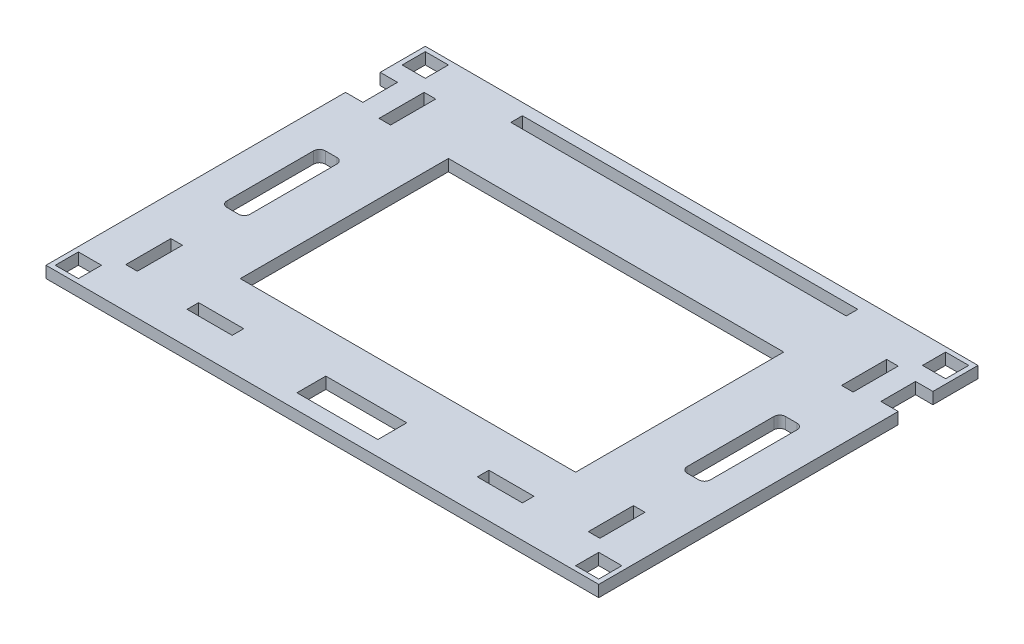
SolidWorks part; units mm, degrees
ref_plane "Front Plane" through (0, 0, 0) normal (0, 0, 1) x (1, 0, 0)
ref_plane "Top Plane" through (0, 0, 0) normal (0, 1, 0) x (1, 0, 0)
ref_plane "Right Plane" through (0, 0, 0) normal (1, 0, 0) x (0, 0, -1)
sketch "Sketch1" plane through (0, 0, 0) normal (0, 1, 0) x (1, 0, 0)
  line L1 (-239, 146.2945) -> (239, 146.2945)
  line L2 (-239, 146.2945) -> (-239, -181.7055)
  line L3 (-239, -181.7055) -> (239, -181.7055)
  line L4 (239, 146.2945) -> (239, -181.7055)
  dimension "D1" = 328
  dimension "D2" = 478
extrude "Boss-Extrude1" add sketch "Sketch1" along normal blind 10
sketch "Sketch2" plane through (0, 10, 0) normal (0, 1, 0) x (1, 0, 0)
  line L0 (239, 146.2945) -> (-239, 146.2945) construction
  line L1 (-235, 142.2945) -> (-215, 142.2945)
  line L2 (-235, 142.2945) -> (-235, 122.2945)
  line L3 (-235, 122.2945) -> (-215, 122.2945)
  line L4 (-215, 142.2945) -> (-215, 122.2945)
  line L5 (-239, 146.2945) -> (-239, -181.7055) construction
  line L6 (-235, -157.7055) -> (-215, -157.7055)
  line L7 (-235, -157.7055) -> (-235, -177.7055)
  line L8 (-235, -177.7055) -> (-215, -177.7055)
  line L9 (-215, -157.7055) -> (-215, -177.7055)
  line L10 (-239, -181.7055) -> (239, -181.7055) construction
  line L11 (215, 142.2945) -> (235, 142.2945)
  line L12 (215, 142.2945) -> (215, 122.2945)
  line L13 (215, 122.2945) -> (235, 122.2945)
  line L14 (235, 142.2945) -> (235, 122.2945)
  line L15 (215, -157.7055) -> (235, -157.7055)
  line L16 (215, -157.7055) -> (215, -177.7055)
  line L17 (215, -177.7055) -> (235, -177.7055)
  line L18 (235, -157.7055) -> (235, -177.7055)
  line L19 (239, -181.7055) -> (239, 146.2945) construction
  dimension "D1" = 20
  dimension "D2" = 20
  dimension "D3" = 4
  dimension "D4" = 4
  dimension "D5" = 4
  dimension "D6" = 4
  dimension "D7" = 20
  dimension "D8" = 20
  dimension "D9" = 20
  dimension "D10" = 4
  dimension "D11" = 4
  dimension "D12" = 20
  dimension "D13" = 4
  dimension "D14" = 4
  dimension "D15" = 20
  dimension "D16" = 20
extrude "Cut-Extrude1" cut sketch "Sketch2" against normal up to next
sketch "Sketch3" plane through (0, 10, 0) normal (0, 1, 0) x (1, 0, 0)
  line L0 (239, -17.7055) -> (-239, -17.7055) construction
  line L1 (239, -181.7055) -> (239, 146.2945) construction
  line L2 (-239, 146.2945) -> (-239, -181.7055) construction
  line L3 (0, 168.3588) -> (0, -221.3758) construction
  line L4 (239, 146.2945) -> (-239, 146.2945) construction
  line L5 (-145, 126.2945) -> (145, 126.2945)
  line L6 (-145, 126.2945) -> (-145, 136.2945)
  line L7 (-145, 136.2945) -> (145, 136.2945)
  line L8 (145, 136.2945) -> (145, 126.2945)
  line L9 (0, 126.2945) -> (-195, 126.2945) construction
  line L10 (-195, 111.2945) -> (-205, 111.2945)
  line L11 (-205, 111.2945) -> (-205, 72.2945)
  line L12 (-205, 72.2945) -> (-195, 72.2945)
  line L13 (-195, 72.2945) -> (-195, 111.2945)
  line L14 (-195, 126.2945) -> (-195, 119.0463) construction
  line L15 (195, 72.2945) -> (195, 111.2945)
  line L16 (205, 72.2945) -> (195, 72.2945)
  line L17 (205, 111.2945) -> (205, 72.2945)
  line L18 (195, 111.2945) -> (205, 111.2945)
  line L19 (195, -146.7055) -> (205, -146.7055)
  line L20 (205, -146.7055) -> (205, -107.7055)
  line L21 (205, -107.7055) -> (195, -107.7055)
  line L22 (195, -107.7055) -> (195, -146.7055)
  line L23 (-195, -107.7055) -> (-195, -146.7055)
  line L24 (-205, -107.7055) -> (-195, -107.7055)
  line L25 (-205, -146.7055) -> (-205, -107.7055)
  line L26 (-195, -146.7055) -> (-205, -146.7055)
  line L27 (-145, -143.7055) -> (-106, -143.7055)
  line L28 (-145, -143.7055) -> (-145, -153.7055)
  line L29 (-145, -153.7055) -> (-106, -153.7055)
  line L30 (145, -153.7055) -> (145, -143.7055)
  line L31 (-106, -143.7055) -> (-106, -153.7055)
  line L32 (106, -143.7055) -> (106, -153.7055)
  line L33 (106, -153.7055) -> (145, -153.7055)
  line L34 (106, -143.7055) -> (145, -143.7055)
  line L35 (35, -143.7055) -> (-35, -143.7055)
  line L36 (-35, -143.7055) -> (-35, -168.7055)
  line L37 (-35, -168.7055) -> (35, -168.7055)
  line L38 (35, -168.7055) -> (35, -143.7055)
  line L39 (209, 24.7945) -> (189, -60.2055) construction
  line L40 (-204, -60.2055) -> (-194, -60.2055)
  line L41 (-209, -55.2055) -> (-209, 19.7945)
  line L42 (-204, 24.7945) -> (-194, 24.7945)
  line L43 (-189, -55.2055) -> (-189, 19.7945)
  line L44 (-209, -60.2055) -> (-189, 24.7945) construction
  line L45 (-209, 24.7945) -> (-189, -60.2055) construction
  line L46 (209, -60.2055) -> (189, 24.7945) construction
  line L47 (189, -55.2055) -> (189, 19.7945)
  line L48 (204, 24.7945) -> (194, 24.7945)
  line L49 (209, -55.2055) -> (209, 19.7945)
  line L50 (204, -60.2055) -> (194, -60.2055)
  line L51 (145, 72.2945) -> (-145, 72.2945)
  line L52 (-145, 72.2945) -> (-145, -107.7055)
  line L53 (-145, -107.7055) -> (145, -107.7055)
  line L54 (145, -107.7055) -> (145, 72.2945)
  line L55 (-239, 107.2945) -> (-224, 107.2945)
  line L56 (-224, 107.2945) -> (-224, 77.2945)
  line L57 (-224, 77.2945) -> (-239, 77.2945)
  line L58 (-235, 122.2945) -> (-215, 122.2945) construction
  line L59 (-239, 107.2945) -> (-239, 77.2945)
  line L60 (239, 107.2945) -> (239, 77.2945)
  line L61 (224, 77.2945) -> (239, 77.2945)
  line L62 (224, 107.2945) -> (224, 77.2945)
  line L63 (239, 107.2945) -> (224, 107.2945)
  arc A0 (-209, -55.2055) -> (-204, -60.2055) centre (-204, -55.2055) ccw
  arc A1 (-194, -60.2055) -> (-189, -55.2055) centre (-194, -55.2055) ccw
  arc A2 (-189, 19.7945) -> (-194, 24.7945) centre (-194, 19.7945) ccw
  arc A3 (-209, 19.7945) -> (-204, 24.7945) centre (-204, 19.7945) cw
  arc A4 (209, 19.7945) -> (204, 24.7945) centre (204, 19.7945) ccw
  arc A5 (189, 19.7945) -> (194, 24.7945) centre (194, 19.7945) cw
  arc A6 (194, -60.2055) -> (189, -55.2055) centre (194, -55.2055) cw
  arc A7 (209, -55.2055) -> (204, -60.2055) centre (204, -55.2055) cw
  point P9 (0, 126.2945)
  point P14 (0, 126.2945)
  point P46 (-199, -17.7055)
  point P82 (199, -17.7055)
  dimension "D20" = 5
  dimension "D1" = 20
  dimension "D2" = 290
  dimension "D3" = 10
  dimension "D4" = 195
  dimension "D5" = 39
  dimension "D6" = 10
  dimension "D7" = 15
  dimension "D8" = 270
  dimension "D9" = 10
  dimension "D10" = 50
  dimension "D11" = 50
  dimension "D12" = 39
  dimension "D13" = 39
  dimension "D14" = 70
  dimension "D15" = 25
  dimension "D16" = 35
  dimension "D17" = 30
  dimension "D18" = 20
  dimension "D19" = 85
  dimension "D21" = 15
  dimension "D22" = 15
  dimension "D23" = 30
extrude "Cut-Extrude2" cut sketch "Sketch3" against normal up to next
